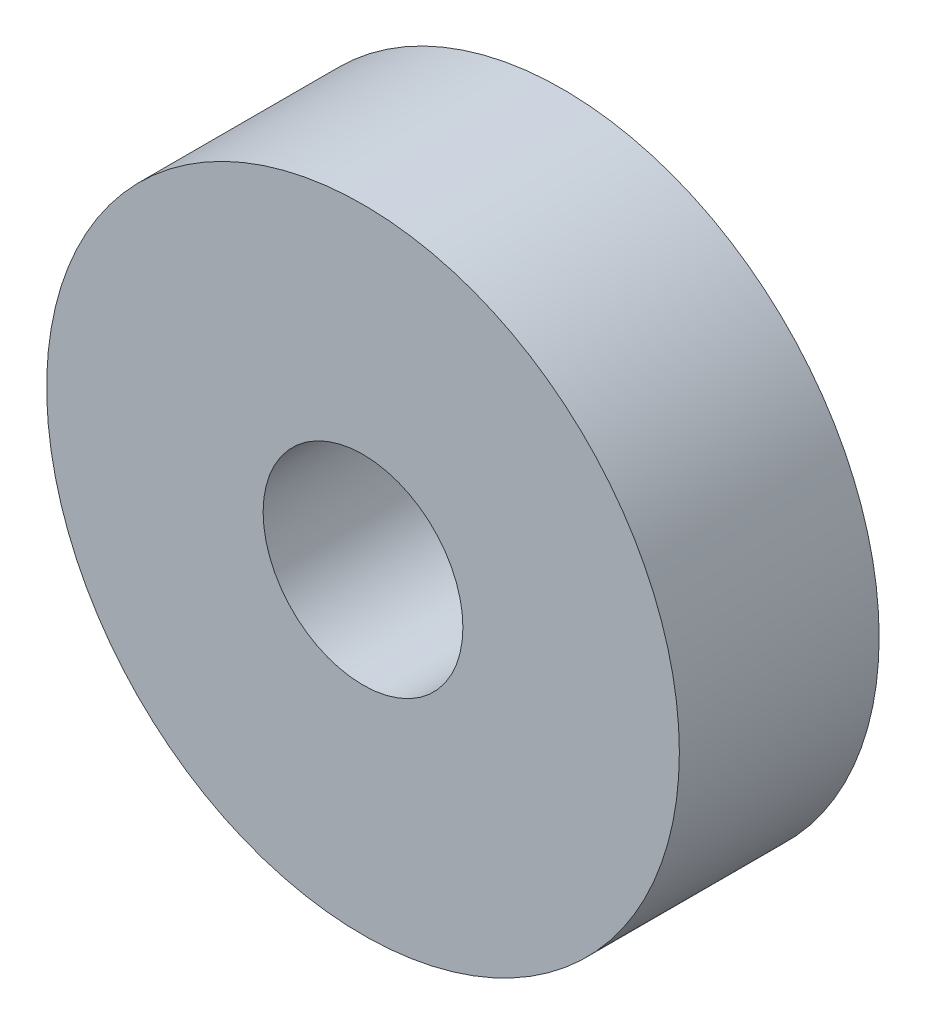
SolidWorks part; units mm, degrees
ref_plane "Alzado" through (0, 0, 0) normal (0, 0, 1) x (1, 0, 0)
ref_plane "Planta" through (0, 0, 0) normal (0, 1, 0) x (1, 0, 0)
ref_plane "Vista lateral" through (0, 0, 0) normal (1, 0, 0) x (0, 0, -1)
sketch "Croquis1" plane through (0, 0, 0) normal (0, 0, 1) x (1, 0, 0)
  circle A0 centre (0, 0) radius 3
  circle A1 centre (0, 0) radius 9.5
  dimension "D1" = 19
  dimension "D2" = 6
extrude "Saliente-Extruir1" add sketch "Croquis1" along normal blind 6
